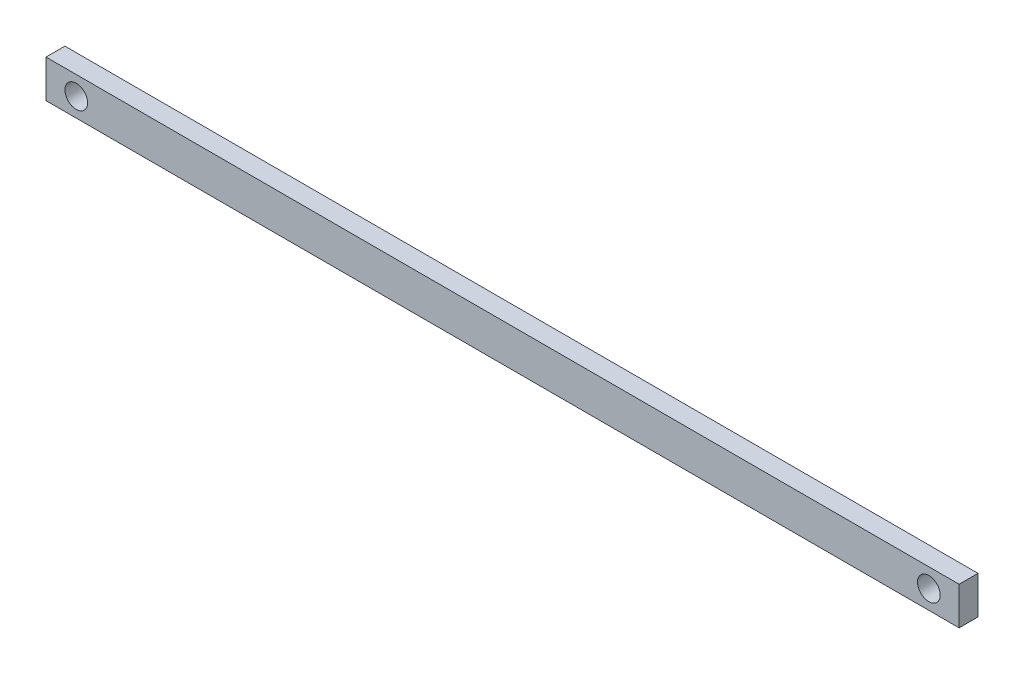
SolidWorks part; units mm, degrees
ref_plane "Front Plane" through (0, 0, 0) normal (0, 0, 1) x (1, 0, 0)
ref_plane "Top Plane" through (0, 0, 0) normal (0, 1, 0) x (1, 0, 0)
ref_plane "Right Plane" through (0, 0, 0) normal (1, 0, 0) x (0, 0, -1)
sketch "Sketch1" plane through (0, 0, 0) normal (0, 0, 1) x (1, 0, 0)
  line L0 (-574.901, 0) -> (570.1823, 0) construction
  line L1 (0, 272.1146) -> (0, -319.3021) construction
  line L3 (-302, 12.5) -> (302, 12.5)
  line L4 (-302, 12.5) -> (-302, -12.5)
  line L5 (-302, -12.5) -> (302, -12.5)
  line L6 (302, 12.5) -> (302, -12.5)
  circle A0 centre (-282, 0) radius 7.5
  circle A1 centre (282, 0) radius 7.5
  point P5 (0, 0)
  dimension "D5" = 282
  dimension "D4" = 15
  dimension "D6" = 15
  dimension "D1" = 604
  dimension "D2" = 25
  dimension "D3" = 282
extrude "Boss-Extrude1" add sketch "Sketch1" along normal blind 25
sketch "Sketch2" plane through (302, 0, 0) normal (1, 0, 0) x (0, 0, -1)
  line L0 (0, -12.5) -> (0, 12.5)
  line L1 (0, 12.5) -> (-12.5, 12.5)
  line L2 (-25, 12.5) -> (0, 12.5) construction
  line L3 (-12.5, 12.5) -> (-12.5, -12.5)
  line L4 (-25, -12.5) -> (0, -12.5) construction
  line L5 (-12.5, -12.5) -> (0, -12.5)
extrude "Cut-Extrude1" cut sketch "Sketch2" against normal through all both and the other way through all
